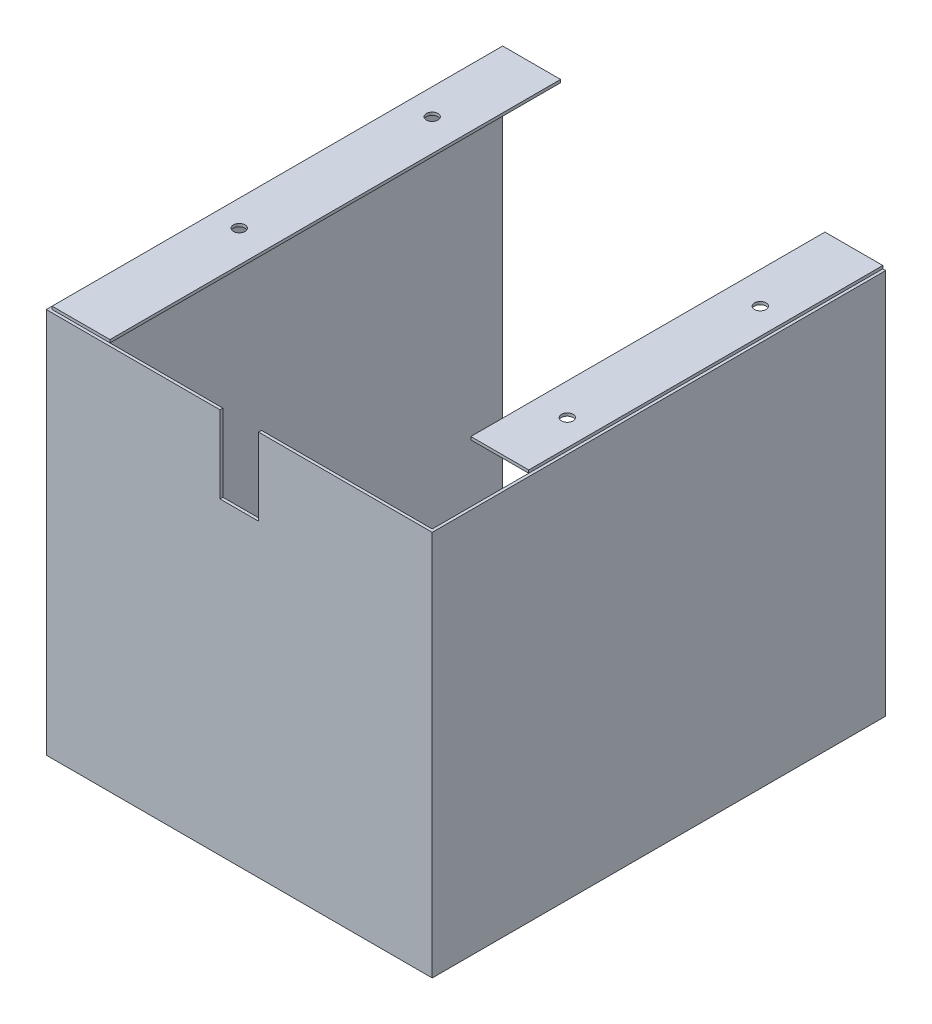
SolidWorks part; units mm, degrees
ref_plane "Front Plane" through (0, 0, 0) normal (0, 0, 1) x (1, 0, 0)
ref_plane "Top Plane" through (0, 0, 0) normal (0, 1, 0) x (1, 0, 0)
ref_plane "Right Plane" through (0, 0, 0) normal (1, 0, 0) x (0, 0, -1)
sketch "Sketch1" plane through (0, 0, 0) normal (0, 0, 1) x (1, 0, 0)
  line L1 (100, -100) -> (-100, -100)
  line L2 (100, -100) -> (100, 100)
  line L3 (100, 100) -> (-100, 100)
  line L4 (-100, -100) -> (-100, 100)
  line L5 (100, -100) -> (-100, 100) construction
  line L6 (100, 100) -> (-100, -100) construction
  point P0 (0, 0)
  dimension "D1" = 200
  dimension "D2" = 200
extrude "Boss-Extrude1" add sketch "Sketch1" along normal blind 235
shell "Shell1" thickness 1.5
sketch "Sketch2" plane through (0, 0, 235) normal (0, 0, 1) x (1, 0, 0)
  line L0 (0, 0) -> (0, 100) construction
  line L1 (100, 100) -> (-100, 100) construction
  line L3 (-10, 100) -> (10, 100)
  line L4 (-10, 100) -> (-10, 60)
  line L5 (-10, 60) -> (10, 60)
  line L6 (10, 100) -> (10, 60)
  dimension "D1" = 20
  dimension "D2" = 10
  dimension "D3" = 40
extrude "Cut-Extrude1" cut sketch "Sketch2" against normal up to next
sketch "Sketch3" plane through (0, 100, 0) normal (0, 1, 0) x (1, 0, 0)
  line L0 (-98.5, -233.5) -> (98.5, -233.5) construction
  line L1 (-98.5, 0) -> (-68.5, 0)
  line L2 (-98.5, 0) -> (-98.5, -233.5)
  line L3 (-98.5, -233.5) -> (-68.5, -233.5)
  line L4 (-68.5, 0) -> (-68.5, -233.5)
  line L5 (68.5, -183.5) -> (98.5, -183.5)
  line L6 (98.5, 0) -> (68.5, 0)
  line L7 (98.5, 0) -> (98.5, -183.5)
  line L9 (68.5, 0) -> (68.5, -183.5)
  line L10 (98.5, -233.5) -> (10, -233.5) construction
  dimension "D1" = 30
  dimension "D2" = 30
  dimension "D3" = 50
extrude "Boss-Extrude2" add sketch "Sketch3" along normal blind 1.5 separate body
sketch "Sketch5" plane through (0, 101.5, 0) normal (0, 1, 0) x (1, 0, 0)
  line L0 (0, 0) -> (0, -233.5) construction
  line L1 (10, -233.5) -> (-10, -233.5) construction
  line L2 (-100, -235) -> (-100, 0) construction
  line L4 (-68.5, 0) -> (-98.5, 0) construction
  circle A0 centre (-85, -50) radius 3
  circle A1 centre (-85, -150) radius 3
  circle A2 centre (85, -150) radius 3
  circle A3 centre (85, -50) radius 3
  dimension "D1" = 50
  dimension "D2" = 100
  dimension "D3" = 6
  dimension "D4" = 15
extrude "Cut-Extrude3" cut sketch "Sketch5" against normal blind 1.5
